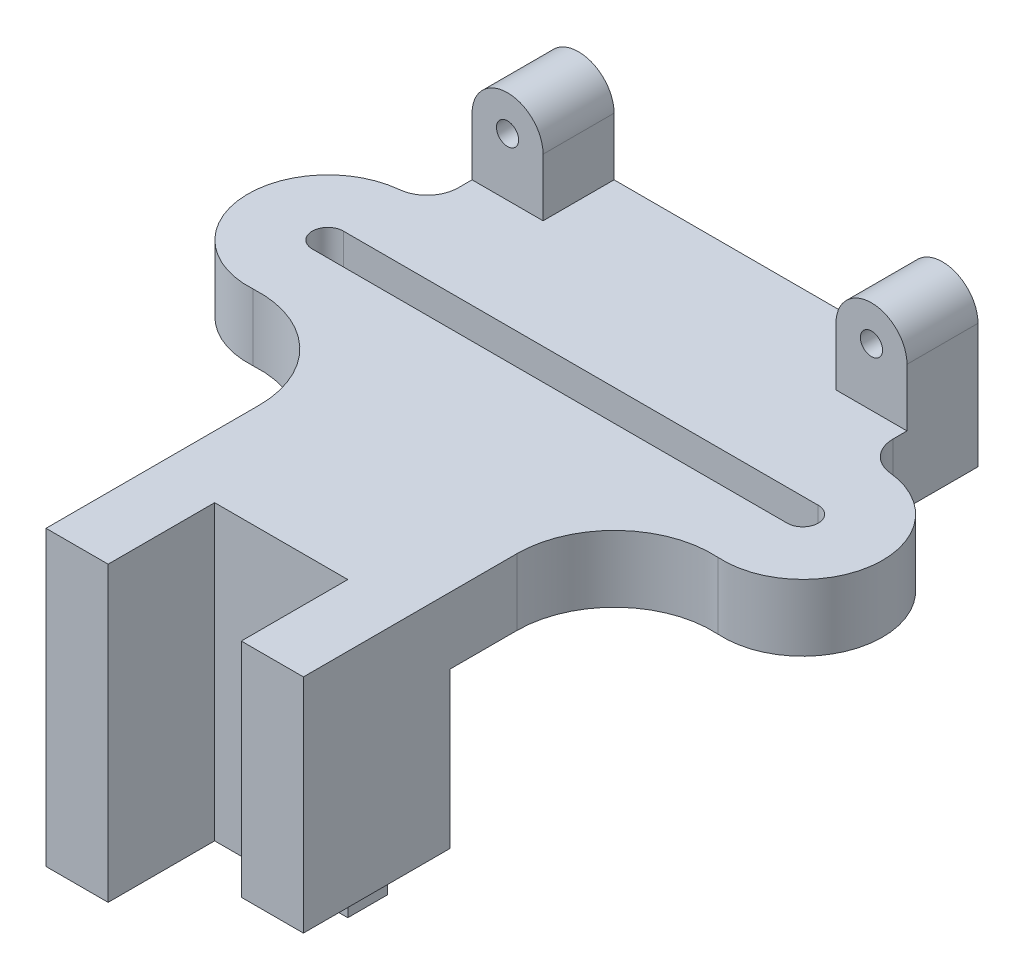
SolidWorks part; units mm, degrees
ref_plane "Front Plane" through (0, 0, 0) normal (0, 0, 1) x (1, 0, 0)
ref_plane "Top Plane" through (0, 0, 0) normal (0, 1, 0) x (1, 0, 0)
ref_plane "Right Plane" through (0, 0, 0) normal (1, 0, 0) x (0, 0, -1)
sketch "Sketch1" plane through (0, 0, 0) normal (0, 1, 0) x (1, 0, 0)
  line L0 (49, 0) -> (-49, 0)
  line L1 (-49, 0) -> (-49, -19.1253)
  line L2 (49, 0) -> (49, -19.1253)
  line L3 (-53.5, -44) -> (53.5, -44) construction
  line L4 (-53.5, -40.5) -> (53.5, -40.5)
  line L5 (-53.5, -47.5) -> (53.5, -47.5)
  line L6 (-29, -83.9218) -> (-29, -132)
  line L7 (-29, -132) -> (-15, -132)
  line L8 (-15, -132) -> (-15, -108)
  line L9 (-15, -108) -> (15, -108)
  line L10 (15, -108) -> (15, -132)
  line L11 (15, -132) -> (29, -132)
  line L12 (29, -132) -> (29, -83.9218)
  arc A0 (-55.3, -26.0902) -> (-52.375, -61.9648) centre (-53.5, -44) ccw
  arc A1 (55.3, -26.0902) -> (52.375, -61.9648) centre (53.5, -44) cw
  arc A2 (49, -19.1253) -> (55.3, -26.0902) centre (56, -19.1253) ccw
  arc A3 (-49, -19.1253) -> (-55.3, -26.0902) centre (-56, -19.1253) cw
  arc A4 (-53.5, -40.5) -> (-53.5, -47.5) centre (-53.5, -44) ccw
  arc A5 (53.5, -47.5) -> (53.5, -40.5) centre (53.5, -44) ccw
  arc A6 (-52.375, -61.9648) -> (-29, -83.9218) centre (-51, -83.9218) cw
  arc A7 (29, -83.9218) -> (52.375, -61.9648) centre (51, -83.9218) cw
  point P3 (0, 0)
  point P4 (0, 0)
  point P15 (0, -44)
  point P30 (0, 0)
  point P31 (0, 0)
  dimension "D1" = 7
  dimension "D2" = 18
  dimension "D10" = 22
  dimension "D11" = 22
  dimension "D3" = 132
  dimension "D5" = 98
  dimension "D6" = 49
  dimension "D7" = 7
  dimension "D8" = 53.5
  dimension "D9" = 107
  dimension "D12" = 14
  dimension "D13" = 14
  dimension "D14" = 58
  dimension "D15" = 24
  dimension "D16" = 29
  dimension "D17" = 88
  dimension "D18" = 98
  dimension "D19" = 107
extrude "Boss-Extrude1" add sketch "Sketch1" along normal blind 15
sketch "Sketch2" plane through (0, 0, 0) normal (0, 0, 1) x (1, 0, 0)
  line L0 (-49, 15) -> (-49, 28)
  line L1 (-33, 28) -> (-33, 15)
  line L2 (49, 15) -> (-49, 15) construction
  line L3 (-33, 15) -> (-49, 15)
  line L4 (0, -55) -> (0, 55) construction
  line L5 (33, 15) -> (49, 15)
  line L6 (33, 28) -> (33, 15)
  line L7 (49, 15) -> (49, 28)
  arc A0 (-49, 28) -> (-33, 28) centre (-41, 28) cw
  circle A1 centre (-41, 28) radius 2.5
  circle A2 centre (41, 28) radius 2.5
  arc A3 (49, 28) -> (33, 28) centre (41, 28) ccw
  dimension "D2" = 8
  dimension "D3" = 5
  dimension "D1" = 13
extrude "Boss-Extrude2" add sketch "Sketch2" along normal blind 16
sketch "Sketch3" plane through (0, 0, 0) normal (0, -1, 0) x (1, 0, 0)
  line L0 (-15, 108) -> (15, 108)
  line L1 (15, 108) -> (15, 132)
  line L2 (15, 132) -> (29, 132)
  line L3 (29, 132) -> (29, 99)
  line L4 (29, 132) -> (29, 83.9218) construction
  line L5 (29, 99) -> (-29, 99)
  line L6 (-29, 83.9218) -> (-29, 132) construction
  line L7 (-29, 99) -> (-29, 132)
  line L8 (-29, 132) -> (-15, 132)
  line L9 (-15, 132) -> (-15, 108)
  dimension "D1" = 33
extrude "Boss-Extrude3" add sketch "Sketch3" along normal blind 51
sketch "Sketch4" plane through (0, 0, 108) normal (0, 0, 1) x (1, 0, 0)
  line L0 (29, 15) -> (29, -51) construction
  line L1 (15, -51) -> (29, -51)
  line L2 (15, -51) -> (15, -35)
  line L3 (15, -35) -> (29, -35)
  line L4 (29, -51) -> (29, -35)
  line L5 (15, -51) -> (-15, -51) construction
  circle A0 centre (0, -18) radius 4.5
  circle A1 centre (0, -40) radius 4.5
  point P13 (0, 0)
  point P15 (1.4286, -30.1457)
  point P16 (1.9885, -40.2241)
  dimension "D3" = 9
  dimension "D4" = 9
  dimension "D1" = 11
  dimension "D2" = 22
  dimension "D5" = 16
extrude "Cut-Extrude1" cut sketch "Sketch4" against normal through all both and the other way through all
